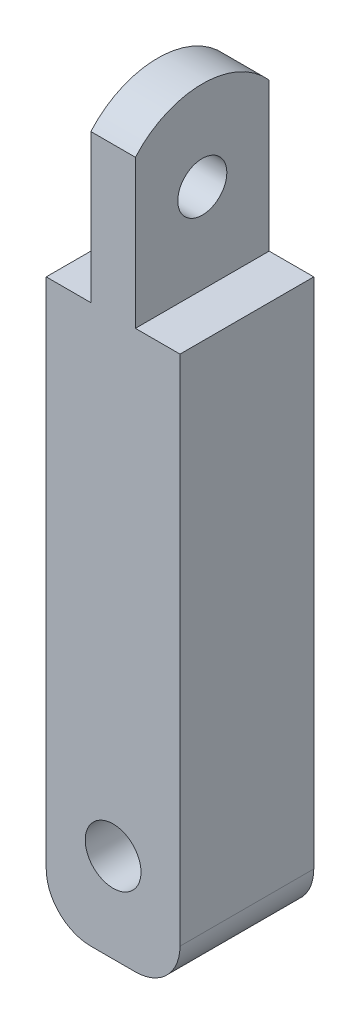
SolidWorks part; units mm, degrees
ref_plane "Front" through (0, 0, 0) normal (0, 0, 1) x (1, 0, 0)
ref_plane "Top" through (0, 0, 0) normal (0, 1, 0) x (1, 0, 0)
ref_plane "Right" through (0, 0, 0) normal (1, 0, 0) x (0, 0, -1)
sketch "Sketch1" plane through (0, 0, 0) normal (0, 0, 1) x (1, 0, 0)
  line L0 (-1, 12.5) -> (-1, 20.5)
  line L1 (-3, -12.5) -> (3, -12.5)
  line L2 (-3, -12.5) -> (-3, 12.5)
  line L3 (-3, 12.5) -> (-1, 12.5)
  line L4 (3, -12.5) -> (3, 12.5)
  line L5 (-3, -12.5) -> (3, 12.5) construction
  line L6 (-3, 12.5) -> (3, -12.5) construction
  line L7 (-1, 20.5) -> (1, 20.5)
  line L8 (1, 20.5) -> (1, 12.5)
  line L9 (0, 0) -> (0, 20.5) construction
  line L10 (1, 12.5) -> (3, 12.5)
  point P0 (0, 0)
  dimension "D1" = 6
  dimension "D2" = 25
  dimension "D3" = 8
  dimension "D4" = 2
extrude "Boss-Extrude1" add sketch "Sketch1" along normal blind 6
sketch "Sketch2" plane through (0, 0, 6) normal (0, 0, 1) x (1, 0, 0)
  line L0 (0, -12.5) -> (0, -8.5) construction
  line L1 (-3, -12.5) -> (3, -12.5) construction
  circle A0 centre (0, -8.5) radius 1.25
  dimension "D1" = 2.5
  dimension "D2" = 4
extrude "Cut-Extrude1" cut sketch "Sketch2" against normal through all
sketch "Sketch3" plane through (0, 0, 0) normal (0, 0, -1) x (-1, 0, 0)
  line L0 (0, -8.5) -> (0, -6.0751) construction
  line L1 (0, -6.0751) -> (-2.1, -7.2876)
  line L2 (-2.1, -7.2876) -> (-2.1, -9.7124)
  line L3 (-2.1, -9.7124) -> (0, -10.9249)
  line L4 (0, -10.9249) -> (2.1, -9.7124)
  line L5 (2.1, -9.7124) -> (2.1, -7.2876)
  line L6 (2.1, -7.2876) -> (0, -6.0751)
  circle A0 centre (0, -8.5) radius 2.1 construction
  dimension "D1" = 4.2
extrude "Cut-Extrude2" cut sketch "Sketch3" against normal blind 2.5
sketch "Sketch4" plane through (-1, 0, 0) normal (-1, 0, 0) x (0, 0, 1)
  line L0 (0, 20.5) -> (6, 12.5) construction
  circle A0 centre (3, 16.5) radius 1.1
  dimension "D1" = 2.2
extrude "Cut-Extrude3" cut sketch "Sketch4" against normal through all
sketch "Sketch5" plane through (-1, 0, 0) normal (-1, 0, 0) x (0, 0, 1)
  line L0 (0, 20.5) -> (0, 12.5) construction
  line L1 (6, 20.5) -> (6, 12.5) construction
  line L2 (6, 20.5) -> (0, 20.5) construction
  line L3 (0, 19.1458) -> (0, 20.5)
  line L4 (0, 20.5) -> (6, 20.5)
  line L5 (6, 20.5) -> (6, 19.1458)
  arc A0 (0, 19.1458) -> (6, 19.1458) centre (3, 16.5) cw
  line M2 (0, 20.5) -> (0, 12.5)
  line M4 (6, 12.5) -> (6, 20.5)
  line M5 (6, 20.5) -> (0, 20.5)
extrude "Cut-Extrude4" cut sketch "Sketch5" against normal through all contours A0 M5 M4 | A0 L4 M2
fillet "Fillet1" radius 2 2 edges at (3, -12.5, 3) (-3, -12.5, 3)
